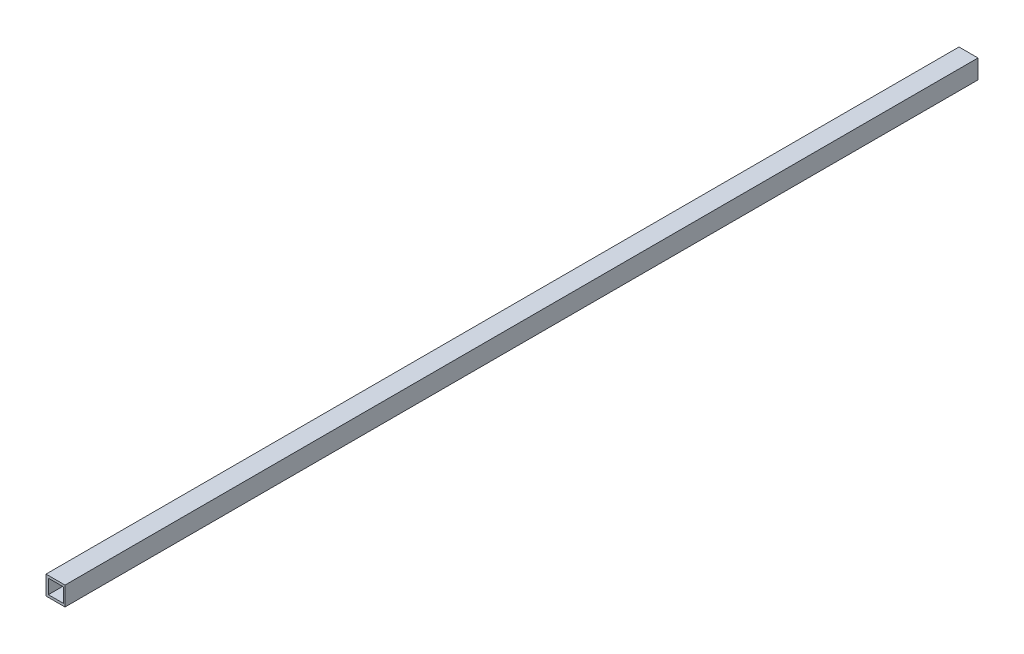
SolidWorks part; units mm, degrees
ref_plane "Front Plane" through (0, 0, 0) normal (0, 0, 1) x (1, 0, 0)
ref_plane "Top Plane" through (0, 0, 0) normal (0, 1, 0) x (1, 0, 0)
ref_plane "Right Plane" through (0, 0, 0) normal (1, 0, 0) x (0, 0, -1)
sketch "Sketch1" plane through (0, 0, 0) normal (0, 0, 1) x (1, 0, 0)
  line L1 (0, 0) -> (25.4, 0)
  line L2 (0, 0) -> (0, 25.4)
  line L3 (0, 25.4) -> (25.4, 25.4)
  line L4 (25.4, 0) -> (25.4, 25.4)
  dimension "D1" = 25.4
  dimension "D2" = 25.4
extrude "Boss-Extrude2" add sketch "Sketch1" along normal blind 1219.2 contours L3 L4 L1 L2
sketch "Sketch2" plane through (0, 0, 0) normal (0, 0, -1) x (-1, 0, 0)
  line L0 (-23.4778, 22.225) -> (-3.175, 22.225)
  line L1 (-23.4778, 22.225) -> (-23.4778, 3.175)
  line L2 (-23.4778, 3.175) -> (-3.175, 3.175)
  line L3 (-3.175, 22.225) -> (-3.175, 3.175)
  line L4 (0, 0) -> (0, 25.4) construction
  line L5 (0, 0) -> (-25.4, 0) construction
  dimension "D1" = 3.175
  dimension "D2" = 3.175
extrude "Cut-Extrude1" cut sketch "Sketch2" against normal through all
